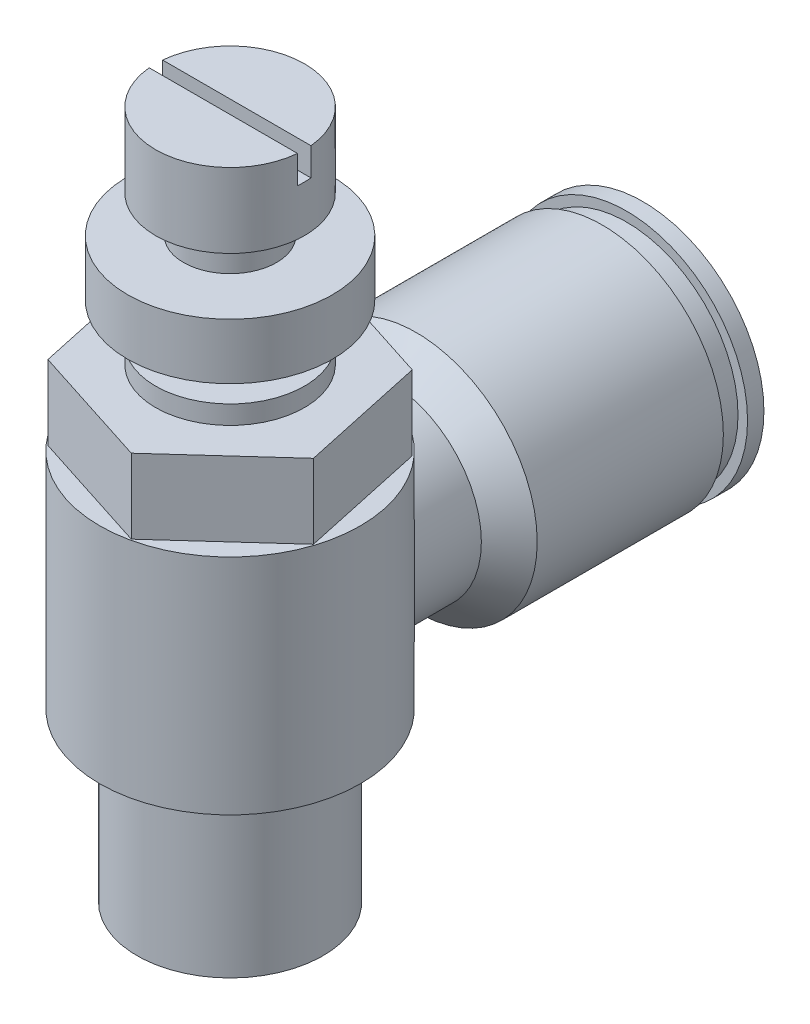
SolidWorks part; units mm, degrees
ref_plane "前视基准面" through (0, 0, 0) normal (0, 0, 1) x (1, 0, 0)
ref_plane "上视基准面" through (0, 0, 0) normal (0, 1, 0) x (1, 0, 0)
ref_plane "右视基准面" through (0, 0, 0) normal (1, 0, 0) x (0, 0, -1)
sketch "草图1" plane through (0, 0, 0) normal (0, 1, 0) x (1, 0, 0)
  circle A0 centre (0, 0) radius 5
  dimension "D1" = 10
extrude "拉伸1" add sketch "草图1" along normal blind 21
sketch "草图2" plane through (0, 21, 0) normal (0, 1, 0) x (1, 0, 0)
  line L1 (5.1323, 4.654) -> (-1.4643, 6.7717)
  line L2 (-1.4643, 6.7717) -> (-6.5966, 2.1177)
  line L3 (-6.5966, 2.1177) -> (-5.1323, -4.654)
  line L4 (-5.1323, -4.654) -> (1.4643, -6.7717)
  line L5 (1.4643, -6.7717) -> (6.5966, -2.1177)
  line L6 (6.5966, -2.1177) -> (5.1323, 4.654)
  circle A0 centre (0, 0) radius 6 construction
  dimension "D1" = 12
extrude "拉伸2" add sketch "草图2" along normal blind 4
sketch "草图3" plane through (0, 25, 0) normal (0, 1, 0) x (1, 0, 0)
  circle A0 centre (0, 0) radius 4
  dimension "D1" = 8
extrude "拉伸3" add sketch "草图3" along normal blind 1
sketch "草图4" plane through (0, 26, 0) normal (0, 1, 0) x (1, 0, 0)
  circle A0 centre (0, 0) radius 2.5
  dimension "D1" = 5
extrude "拉伸4" add sketch "草图4" along normal blind 7
sketch "草图5" plane through (0, 33, 0) normal (0, 1, 0) x (1, 0, 0)
  circle A0 centre (0, 0) radius 4
  dimension "D1" = 8
extrude "拉伸5" add sketch "草图5" along normal blind 4
ref_plane "基准面1" through (0, 28, 0) normal (0, 1, 0) x (-1, 0, 0)
sketch "草图6" plane through (0, 28, 0) normal (0, 1, 0) x (-1, 0, 0)
  circle A0 centre (0, 0) radius 5.5
  dimension "D1" = 11
extrude "拉伸6" add sketch "草图6" along normal blind 3
sketch "草图7" plane through (0, 21, 0) normal (0, -1, 0) x (1, 0, 0)
  circle A0 centre (0, 0) radius 7
  circle A1 centre (0, 0) radius 5
  dimension "D1" = 14
extrude "拉伸7" add sketch "草图7" along normal blind 12 separate body
sketch "草图8" plane through (0, 0, 0) normal (1, 0, 0) x (0, 0, -1)
  line L0 (0, 15) -> (23.5494, 15) construction
  line L1 (3.8771, 18.847) -> (3.8771, 20)
  line L2 (3.8771, 20) -> (5.0733, 20)
  line L3 (8.5, 20) -> (10, 21.5)
  line L4 (10, 21.5) -> (20, 21.5)
  line L5 (20, 21.5) -> (20, 20.988)
  line L6 (20, 20.988) -> (21.3, 20.988)
  line L7 (21.3, 20.988) -> (21.3, 21.5)
  line L8 (21.3, 21.5) -> (22.1802, 21.5)
  line L9 (22.1802, 21.5) -> (22.1802, 20)
  line L10 (22.1802, 20) -> (11.7747, 20)
  line L11 (11.7747, 20) -> (9.9985, 18.847)
  line L12 (9.9985, 18.847) -> (3.8771, 18.847)
  line L13 (5.0733, 20) -> (8.5, 20)
  line L14 (-7, 9) -> (7, 9) construction
  line L15 (7, 9) -> (7, 21) construction
  line L16 (7, 9) -> (7, 21) construction
  dimension "D1" = 6
  dimension "D2" = 5
  dimension "D3" = 6.5
  dimension "D4" = 3
  dimension "D5" = 1.5
  dimension "D6" = 10
  dimension "D7" = 1.3
revolve "旋转1" add sketch "草图8" angle 360 about L0
sketch "草图9" plane through (0, 37, 0) normal (0, 1, 0) x (1, 0, 0)
  line L1 (-4.6644, -0.3609) -> (4.6644, -0.3609)
  line L2 (-4.6644, -0.3609) -> (-4.6644, 0.3609)
  line L3 (-4.6644, 0.3609) -> (4.6644, 0.3609)
  line L4 (4.6644, -0.3609) -> (4.6644, 0.3609)
  line L5 (-4.6644, -0.3609) -> (4.6644, 0.3609) construction
  line L6 (-4.6644, 0.3609) -> (4.6644, -0.3609) construction
  point P0 (0, 0)
extrude "拉伸9" cut sketch "草图9" against normal blind 1.5
sketch "草图10" plane through (0, 0, 0) normal (0, -1, 0) x (1, 0, 0)
  circle A0 centre (0, 0) radius 4.2724
extrude "拉伸10" cut sketch "草图10" against normal blind 19
